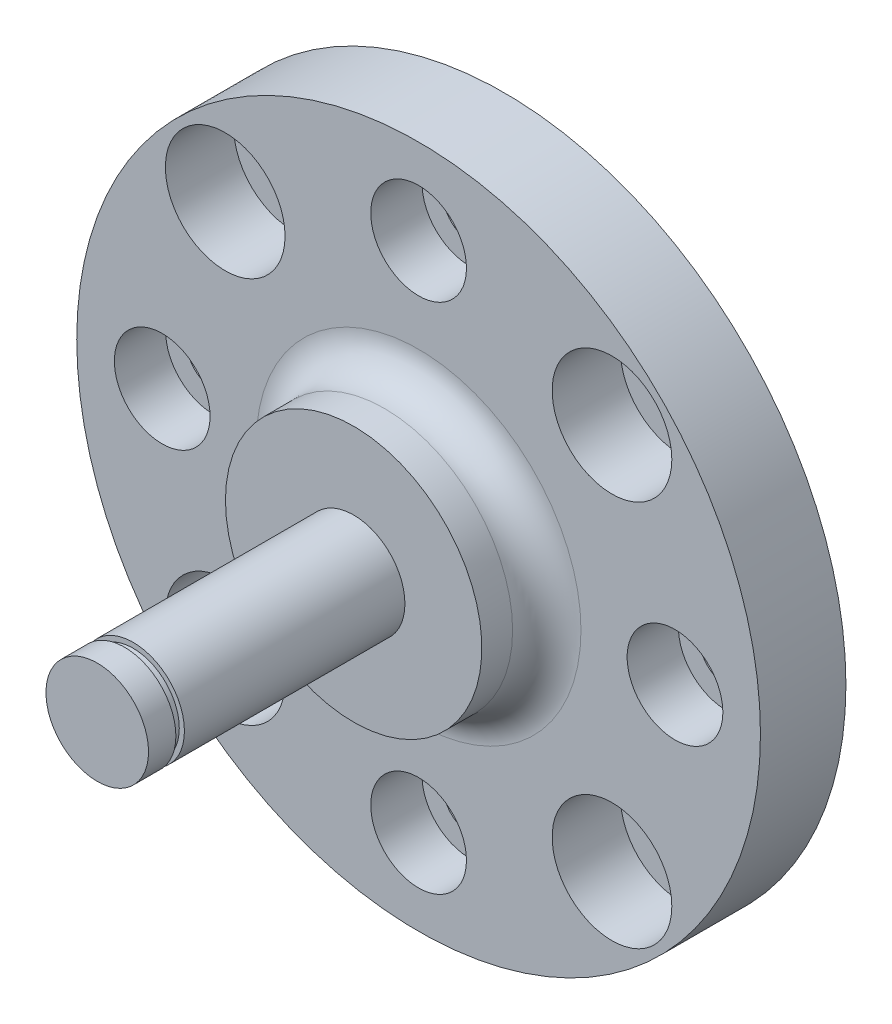
SolidWorks part; units mm, degrees
ref_plane "前视基准面" through (0, 0, 0) normal (0, 0, 1) x (1, 0, 0)
ref_plane "上视基准面" through (0, 0, 0) normal (0, 1, 0) x (1, 0, 0)
ref_plane "右视基准面" through (0, 0, 0) normal (1, 0, 0) x (0, 0, -1)
sketch "草图1" plane through (0, 0, 0) normal (0, 0, 1) x (1, 0, 0)
  line L0 (0, 0) -> (0, 15) construction
  line L1 (0, 0) -> (-11.3137, 11.3137) construction
  circle A0 centre (0, 0) radius 20
  circle A1 centre (0, 0) radius 16 construction
  circle A2 centre (0, 0) radius 15 construction
  circle A3 centre (0, 15) radius 1.55
  circle A4 centre (-11.3137, 11.3137) radius 2.05
  circle A5 centre (11.3137, 11.3137) radius 2.05
  circle A6 centre (15, 0) radius 1.55
  circle A7 centre (11.3137, -11.3137) radius 2.05
  circle A8 centre (0, -15) radius 1.55
  circle A9 centre (-11.3137, -11.3137) radius 2.05
  circle A10 centre (-15, 0) radius 1.55
  point P24 (0, 0)
  dimension "D1" = 40
  dimension "D2" = 30
  dimension "D3" = 32
  dimension "D4" = 3.1
  dimension "D6" = 4.1
  dimension "D5" = 45
  dimension "D7" = 4
extrude "凸台-拉伸1" add sketch "草图1" along normal blind 5
sketch "草图2" plane through (0, 0, 5) normal (0, 0, 1) x (1, 0, 0)
  circle A0 centre (0, 15) radius 2.8
  circle A1 centre (15, 0) radius 2.8
  circle A2 centre (0, -15) radius 2.8
  circle A3 centre (-15, 0) radius 2.8
  point P12 (0, 0)
  dimension "D1" = 5.6
  dimension "D2" = 4
extrude "切除-拉伸1" cut sketch "草图2" against normal blind 3
sketch "草图3" plane through (0, 0, 5) normal (0, 0, 1) x (1, 0, 0)
  circle A0 centre (-11.3137, 11.3137) radius 3.5
  circle A1 centre (11.3137, 11.3137) radius 3.5
  circle A2 centre (11.3137, -11.3137) radius 3.5
  circle A3 centre (-11.3137, -11.3137) radius 3.5
  point P12 (0, 0)
  dimension "D1" = 7
  dimension "D2" = 4
extrude "切除-拉伸2" cut sketch "草图3" against normal blind 4
sketch "草图5" plane through (0, 0, 5) normal (0, 0, 1) x (1, 0, 0)
  circle A0 centre (0, 0) radius 7.5
  dimension "D1" = 15
extrude "凸台-拉伸3" add sketch "草图5" along normal blind 3.8
sketch "草图6" plane through (0, 0, 8.8) normal (0, 0, 1) x (1, 0, 0)
  circle A0 centre (0, 0) radius 3
  dimension "D1" = 6
extrude "凸台-拉伸4" add sketch "草图6" along normal blind 15
fillet "圆角1" radius 2 1 edges at (7.5, 0, 5)
ref_plane "基准面4" through (0, 0, 21.7) normal (0, 0, 1) x (1, 0, 0)
sketch "草图7" plane through (0, 0, 21.7) normal (0, 0, 1) x (1, 0, 0)
  circle A0 centre (0, 0) radius 3 construction
  circle A1 centre (0, 0) radius 3
  circle A2 centre (0, 0) radius 2.7
  dimension "D1" = 5.4
extrude "切除-拉伸3" cut sketch "草图7" along normal blind 0.5
